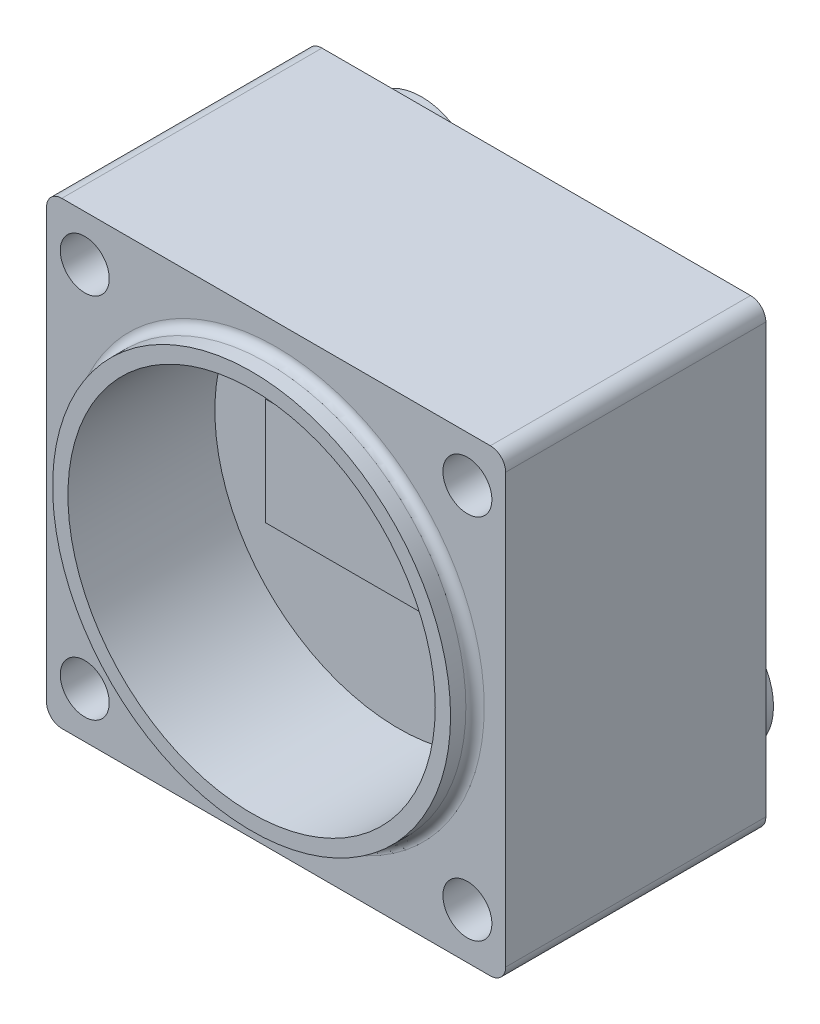
SolidWorks part; units mm, degrees
material "Camera"
ref_plane "Front Plane" through (0, 0, 0) normal (0, 0, 1) x (1, 0, 0)
ref_plane "Top Plane" through (0, 0, 0) normal (0, 1, 0) x (1, 0, 0)
ref_plane "Right Plane" through (0, 0, 0) normal (1, 0, 0) x (0, 0, -1)
sketch "Sketch1" plane through (0, 0, 0) normal (0, 0, 1) x (1, 0, 0)
  line L1 (7.5, -7.5) -> (-7.5, -7.5)
  line L2 (7.5, -7.5) -> (7.5, 7.5)
  line L3 (7.5, 7.5) -> (-7.5, 7.5)
  line L4 (-7.5, -7.5) -> (-7.5, 7.5)
  line L5 (7.5, -7.5) -> (-7.5, 7.5) construction
  line L6 (7.5, 7.5) -> (-7.5, -7.5) construction
  point P0 (0, 0)
  dimension "D1" = 15
  dimension "D2" = 15
extrude "Boss-Extrude1" add sketch "Sketch1" along normal blind 8.5
sketch "Sketch2" plane through (0, 0, 8.5) normal (0, 0, 1) x (1, 0, 0)
  circle A0 centre (0, 0) radius 6
  circle A1 centre (0, 0) radius 6.5
  dimension "D1" = 12
  dimension "D2" = 13
extrude "Boss-Extrude2" add sketch "Sketch2" along normal blind 0.8
fillet "Fillet1" radius 0.3 1 edges at (6.5, 0, 8.5)
sketch "Sketch3" plane through (0, 0, 8.5) normal (0, 0, 1) x (1, 0, 0)
  circle A0 centre (0, 0) radius 6
extrude "Cut-Extrude1" cut sketch "Sketch3" against normal blind 4
fillet "Fillet2" radius 0.5 4 edges at (-7.5, -7.5, 4.25) (7.5, -7.5, 4.25) (7.5, 7.5, 4.25) (-7.5, 7.5, 4.25)
sketch "Sketch4" plane through (0, 0, 4.5) normal (0, 0, 1) x (1, 0, 0)
  line L1 (3.75, -1.75) -> (-3.75, -1.75)
  line L2 (3.75, -1.75) -> (3.75, 1.75)
  line L3 (3.75, 1.75) -> (-3.75, 1.75)
  line L4 (-3.75, -1.75) -> (-3.75, 1.75)
  line L5 (3.75, -1.75) -> (-3.75, 1.75) construction
  line L6 (3.75, 1.75) -> (-3.75, -1.75) construction
  point P0 (0, 0)
  dimension "D1" = 3.5
  dimension "D2" = 7.5
extrude "Boss-Extrude3" add sketch "Sketch4" along normal blind 0.6
hole_wizard "Tap Drill for M2 Tap1" positions "Sketch8" profile "Sketch5" hole size "M2" standard "ISO"
sketch "Sketch8" plane through (0, 0, 8.5) normal (0, 0, 1) x (1, 0, 0)
  line L4 (7, 7.5) -> (-7, 7.5) construction
  line L5 (-7, -7.5) -> (7, -7.5) construction
  point P0 (-6.25, 6)
  point P2 (6.25, 6)
  point P4 (6.25, -6)
  point P6 (-6.25, -6)
  dimension "D1" = 6.25
  dimension "D2" = 12.5
  dimension "D3" = 12.5
  dimension "D4" = 6.25
  dimension "D5" = 1.5
  dimension "D6" = 1.5
  dimension "D7" = 1.5
  dimension "D8" = 1.5
sketch "Sketch5" plane through (-6.25, 6, 8.5) normal (1, 0, 0) x (0, -1, 0)
  line L0 (0, 0) -> (0, 2.5)
  line L1 (0, 2.5) -> (0.8, 2.5)
  line L2 (0.8, 2.5) -> (0.8, 0)
  line L5 (0.8, 0) -> (0, 0)
  line L10 (0, 2.5) -> (-0.8, 2.5) construction
  line L11 (0, -6.35) -> (0, 107.95) construction
  dimension "Hole Dia." = 1.6
  dimension "Hole Depth" = 2.5
  dimension "Drill Angle" = 180
hole_wizard "Tap Drill for M3 Tap1" positions "Sketch10" profile "Sketch9" hole size "M3" standard "ISO"
sketch "Sketch10" plane through (0, 0, 0) normal (0, 0, -1) x (-1, 0, 0)
  line L0 (0, 0) -> (0, 4.1992) construction
  line L3 (0, 0) -> (9.9466, 0) construction
  point P0 (4.75, 4.75)
  point P2 (-4.75, -4.75)
  dimension "D1" = 4.75
  dimension "D2" = 4.75
  dimension "D3" = 4.75
  dimension "D4" = 4.75
sketch "Sketch9" plane through (-4.75, 4.75, 0) normal (1, 0, 0) x (0, 1, 0)
  line L0 (0, 0) -> (0, 2.25)
  line L1 (0, 2.25) -> (1.25, 2.25)
  line L2 (1.25, 2.25) -> (1.25, 0)
  line L5 (1.25, 0) -> (0, 0)
  line L10 (0, 2.25) -> (-1.25, 2.25) construction
  line L11 (0, -6.35) -> (0, 107.95) construction
  dimension "Hole Dia." = 2.5
  dimension "Hole Depth" = 2.25
  dimension "Drill Angle" = 180
sketch "Sketch11" plane through (0, 0, 0) normal (0, 0, -1) x (-1, 0, 0)
  circle A0 centre (-4.75, -4.75) radius 1.25
  circle A1 centre (-4.75, -4.75) radius 2
  circle A2 centre (4.75, 4.75) radius 1.25
  circle A3 centre (4.75, 4.75) radius 2
  dimension "D1" = 4
  dimension "D2" = 4
extrude "Boss-Extrude4" add sketch "Sketch11" along normal blind 1
sketch "Sketch12" plane through (0, 0, 0) normal (0, 0, -1) x (-1, 0, 0)
  line L0 (-5.2, 4) -> (-0.2, 4) construction
  line L1 (-5.2, 5.25) -> (-0.2, 5.25)
  line L2 (-5.2, 5.25) -> (-5.2, 2.75)
  line L3 (-5.2, 2.75) -> (-0.2, 2.75)
  line L4 (-0.2, 5.25) -> (-0.2, 2.75)
  line L5 (-2.7, 5.25) -> (-2.7, 2.75) construction
  dimension "D1" = 4
  dimension "D2" = 2.7
  dimension "D3" = 5
  dimension "D4" = 2.5
extrude "Cut-Extrude2" cut sketch "Sketch12" against normal blind 0.4
sketch "Sketch13" plane through (0, 0, 0.4) normal (0, 0, -1) x (-1, 0, 0)
  text T0 "<b>USB Connector</b>" font "Century Gothic" height in points 1
extrude "Boss-Extrude5" add sketch "Sketch13" along normal blind 0.2
